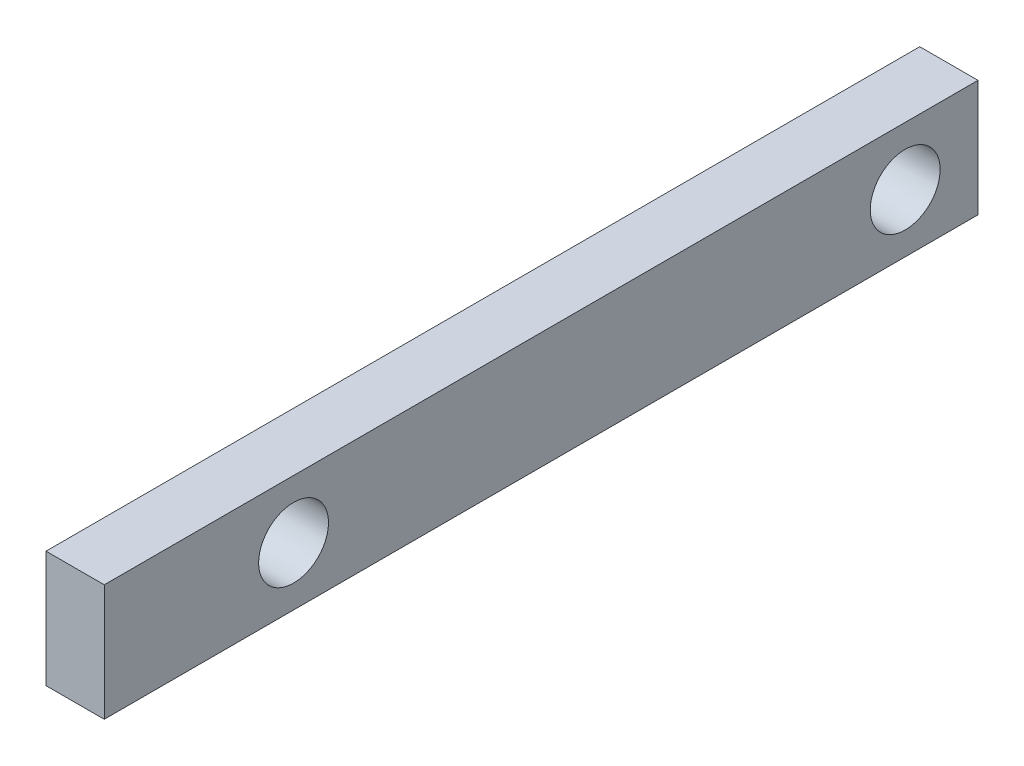
SolidWorks part; units mm, degrees
ref_plane "Front Plane" through (0, 0, 0) normal (0, 0, 1) x (1, 0, 0)
ref_plane "Top Plane" through (0, 0, 0) normal (0, 1, 0) x (1, 0, 0)
ref_plane "Right Plane" through (0, 0, 0) normal (1, 0, 0) x (0, 0, -1)
sketch "Sketch1" plane through (0, 0, 0) normal (1, 0, 0) x (0, 0, -1)
  line L1 (-32.6542, 3.2715) -> (5.4458, 3.2715)
  line L2 (-32.6542, 3.2715) -> (-32.6542, -1.8085)
  line L3 (-32.6542, -1.8085) -> (5.4458, -1.8085)
  line L4 (5.4458, 3.2715) -> (5.4458, -1.8085)
  dimension "D1" = 5.08
  dimension "D2" = 38.1
extrude "Boss-Extrude1" add sketch "Sketch1" along normal blind 2.54
sketch "Sketch2" plane through (0, 0, 0) normal (-1, 0, 0) x (0, 0, 1)
  line L0 (-5.4458, -1.8085) -> (-5.4458, 3.2715) construction
  circle A0 centre (24.3992, 0.7315) radius 1.524
  circle A1 centre (-2.2708, 0.7315) radius 1.524 construction
  circle A2 centre (-2.2708, 0.7315) radius 1.524
  circle A3 centre (24.3992, 0.7315) radius 1.524 construction
  point P6 (-5.4458, 0.7315)
  point P7 (0, 0)
  point P10 (22.227, 0.7315)
  dimension "D1" = 3.175
extrude "Cut-Extrude1" cut sketch "Sketch2" against normal through all
